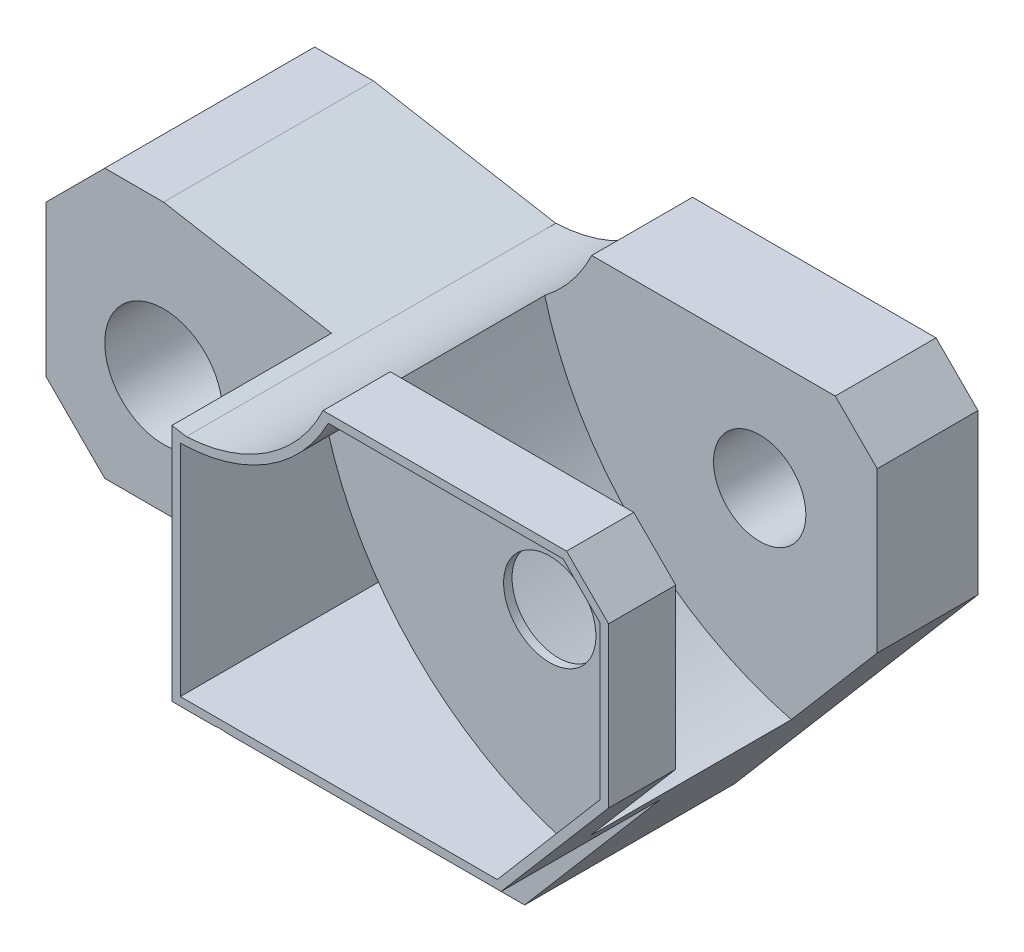
SolidWorks part; units mm, degrees
material "AISI 304"
ref_plane "Plan de face" through (0, 0, 0) normal (0, 0, 1) x (1, 0, 0)
ref_plane "Plan de dessus" through (0, 0, 0) normal (0, 1, 0) x (1, 0, 0)
ref_plane "Plan de droite" through (0, 0, 0) normal (1, 0, 0) x (0, 0, -1)
sketch "Esquisse1" plane through (0, 0, 0) normal (0, 0, 1) x (1, 0, 0)
  line L15 (69.0555, 42.5858) -> (98.0555, 42.5858)
  line L16 (98.0555, 42.5858) -> (103.0555, 37.5858)
  line L17 (103.0555, 37.5858) -> (103.0555, 18.5858)
  line L20 (103.0555, 18.5858) -> (74.0555, -15.4142)
  line L24 (31.0555, 35.5858) -> (52.7651, 31.7578)
  line L25 (31.0555, 35.5858) -> (24.0555, 35.5858)
  line L26 (24.0555, 35.5858) -> (17.0555, 28.5858)
  line L27 (17.0555, 28.5858) -> (17.0555, 10.5858)
  line L28 (17.0555, 10.5858) -> (24.0555, 3.5858)
  line L30 (24.0555, 3.5858) -> (56.0555, 3.5858)
  line L32 (74.0555, -15.4142) -> (68.3525, -15.4142)
  arc A4 (69.0555, 42.5858) -> (52.7651, 31.7578) centre (51.8932, 50.7378) cw
  arc A5 (56.0555, 3.5858) -> (61.7972, -1.9629) centre (56.8345, -1.3532) cw
  arc A7 (61.7972, -1.9629) -> (68.3525, -15.4142) centre (90.2614, 3.5858) ccw
  point P7 (90.2614, 3.5858)
  point P11 (71.204, -15.4142)
  dimension "D8" = 7
  dimension "D9" = 5
  dimension "D6" = 19
  dimension "D14" = 32
  dimension "D15" = 19
  dimension "D10" = 58
  dimension "D12" = 29
  dimension "D2" = 45
  dimension "D3" = 5
  dimension "D4" = 24
  dimension "D5" = 29
  dimension "D7" = 45
  dimension "D11" = 86
  dimension "D13" = 19
  dimension "D16" = 29
  dimension "D19" = 7
  dimension "D20" = 14
  dimension "D21" = 10
extrude "Boss.-Extru.1" add sketch "Esquisse1" along normal blind 44
sketch "Esquisse2" plane through (0, 0, 44) normal (0, 0, 1) x (1, 0, 0)
  line L0 (17.0555, 28.5858) -> (17.0555, 10.5858) construction
  line L1 (24.0555, 3.5858) -> (56.0555, 3.5858) construction
  circle A0 centre (31.0555, 17.5858) radius 7
  point P6 (35.5625, 11.703)
  dimension "D1" = 14
  dimension "D2" = 14
  dimension "D3" = 14
extrude "Enlèv. mat.-Extru.1" cut sketch "Esquisse2" against normal blind 44
sketch "Esquisse3" plane through (0, 0, 44) normal (0, 0, 1) x (1, 0, 0)
  line L0 (17.0555, 28.5858) -> (17.0555, 10.5858)
  line L1 (17.0555, 10.5858) -> (24.0555, 3.5858)
  line L2 (24.0555, 3.5858) -> (51.0555, 3.5858)
  line L3 (24.0555, 3.5858) -> (56.0555, 3.5858) construction
  line L4 (51.0555, 3.5858) -> (51.0555, 32.0592)
  line L5 (52.7651, 31.7578) -> (31.0555, 35.5858) construction
  line L6 (51.0555, 32.0592) -> (31.0555, 35.5858)
  line L7 (31.0555, 35.5858) -> (24.0555, 35.5858)
  line L8 (31.0555, 35.5858) -> (24.0555, 35.5858) construction
  line L9 (24.0555, 35.5858) -> (17.0555, 28.5858)
  dimension "D1" = 34
extrude "Enlèv. mat.-Extru.2" cut sketch "Esquisse3" against normal blind 19
sketch "Esquisse4" plane through (0, 0, 44) normal (0, 0, 1) x (1, 0, 0)
  line L0 (103.0555, 18.5858) -> (103.0555, 37.5858) construction
  line L1 (98.0555, 42.5858) -> (69.0555, 42.5858) construction
  circle A0 centre (89.0555, 28.5858) radius 5.5
  dimension "D1" = 11
  dimension "D2" = 14
  dimension "D3" = 14
extrude "Enlèv. mat.-Extru.3" cut sketch "Esquisse4" against normal blind 50
sketch "Esquisse10" plane through (0, 0, 44) normal (0, 0, 1) x (1, 0, 0)
  line L0 (56.0555, 3.5858) -> (90.2614, 3.5858)
  line L1 (74.0555, -15.4142) -> (103.0555, 18.5858) construction
  line L2 (90.2614, 3.5858) -> (74.0555, -15.4142)
  line L3 (74.0555, -15.4142) -> (68.3525, -15.4142)
  arc A0 (61.7972, -1.9629) -> (56.0555, 3.5858) centre (56.8345, -1.3532) ccw construction
  arc A1 (56.0555, 3.5858) -> (61.7972, -1.9629) centre (56.0555, -2.1592) cw
  arc A2 (61.7972, -1.9629) -> (68.3525, -15.4142) centre (90.2614, 3.5858) ccw
  point P15 (0, 0)
  dimension "D1" = 19
extrude "Enlèv. mat.-Extru.5" cut sketch "Esquisse10" against normal blind 19
sketch "Esquisse11" plane through (0, 0, 44) normal (0, 0, 1) x (1, 0, 0)
  line L0 (103.0555, 37.5858) -> (103.0555, 50.3291)
  line L1 (103.0555, 18.5858) -> (103.0555, 37.5858) construction
  line L2 (103.0555, 37.5858) -> (98.0555, 42.5858) construction
sketch "Esquisse13" plane through (0, 0, 44) normal (0, 0, 1) x (1, 0, 0)
  line L0 (103.0555, 37.5858) -> (103.0555, 50.3291) construction
  line L1 (90.2614, 3.5858) -> (103.0555, 18.5858) construction
  line L2 (98.0555, 42.5858) -> (69.0555, 42.5858) construction
  line L3 (69.0555, 42.5858) -> (98.0555, 42.5858)
  line L4 (98.0555, 42.5858) -> (103.0555, 37.5858)
  line L5 (103.0555, 37.5858) -> (103.0555, 18.5858)
  line L6 (103.0555, 18.5858) -> (92.8202, 6.5858)
  arc A0 (63.4564, 35.6616) -> (92.8202, 6.5858) centre (103.0555, 46.2877) ccw
  arc A1 (52.7651, 31.7578) -> (69.0555, 42.5858) centre (51.8932, 50.7378) ccw construction
  arc A2 (63.4564, 35.6616) -> (69.0555, 42.5858) centre (51.8932, 50.7378) ccw
  dimension "D2" = 41
  dimension "D1" = 36
extrude "Enlèv. mat.-Extru.8" cut sketch "Esquisse13" against normal blind 32
sketch "Esquisse14" plane through (0, 0, 44) normal (0, 0, 1) x (1, 0, 0)
  line L0 (92.8202, 6.5858) -> (103.0555, 18.5858)
  line L1 (103.0555, 18.5858) -> (103.0555, 37.5858)
  line L2 (103.0555, 37.5858) -> (98.0555, 42.5858)
  line L3 (98.0555, 42.5858) -> (69.0555, 42.5858)
  line L4 (103.0555, 37.5858) -> (103.0555, 50.3291) construction
  line L5 (90.2614, 3.5858) -> (92.8202, 6.5858) construction
  arc A0 (63.4564, 35.6616) -> (92.8202, 6.5858) centre (103.0555, 46.2877) ccw
  arc A1 (63.4564, 35.6616) -> (69.0555, 42.5858) centre (51.8932, 50.7378) ccw
  dimension "D2" = 41
  dimension "D1" = 36
extrude "Boss.-Extru.3" add sketch "Esquisse14" against normal blind 8
sketch "Esquisse15" plane through (0, 0, 44) normal (0, 0, 1) x (1, 0, 0)
  circle A0 centre (89.0555, 28.5858) radius 5.5
extrude "Enlèv. mat.-Extru.9" cut sketch "Esquisse15" against normal blind 44
sketch "Esquisse16" plane through (0, 0, 44) normal (0, 0, 1) x (1, 0, 0)
  line L0 (52.0555, 30.7384) -> (52.0555, 5.6949)
  line L1 (52.0555, 4.5858) -> (89.8, 4.5858)
  line L2 (99.8465, 16.3644) -> (102.0555, 18.9543)
  line L3 (102.0555, 19.2104) -> (102.0555, 37.1716)
  line L4 (102.0555, 37.1716) -> (97.6413, 41.5858)
  line L5 (90.2614, 3.5858) -> (57.6135, 3.5858) construction
  line L6 (51.0555, 3.5858) -> (51.0555, 32.0592) construction
  line L7 (52.0555, 5.6949) -> (52.0555, 4.5858)
  line L8 (90.2614, 3.5858) -> (103.0555, 18.5858) construction
  line L9 (89.8, 4.5858) -> (99.8465, 16.3644)
  line L10 (103.0555, 18.5858) -> (103.0555, 37.5858) construction
  line L11 (102.0555, 19.2104) -> (102.0555, 18.9543)
  line L12 (103.0555, 37.5858) -> (98.0555, 42.5858) construction
  line L13 (97.6413, 41.5858) -> (69.7927, 41.5858)
  line L14 (98.0555, 42.5858) -> (69.0555, 42.5858) construction
  line L15 (69.7927, 41.5858) -> (69.6764, 41.5858)
  arc A2 (52.0555, 30.7384) -> (69.6764, 41.5858) centre (51.8932, 50.7378) ccw
  dimension "D1" = 1
  dimension "D2" = 20
  dimension "D3" = 1
  dimension "D4" = 1
  dimension "D5" = 1
  dimension "D6" = 1
  dimension "D7" = 1
  dimension "D8" = 1
extrude "Enlèv. mat.-Extru.10" cut sketch "Esquisse16" against normal blind 7
sketch "Esquisse17" plane through (0, 0, 37) normal (0, 0, 1) x (1, 0, 0)
  line L0 (102.0555, 37.1716) -> (102.0555, 52.765)
  line L1 (89.8, 4.5858) -> (102.0555, 18.9543) construction
  line L2 (97.6413, 41.5858) -> (69.6764, 41.5858) construction
  line L3 (52.0555, 30.7384) -> (52.0555, 4.5858)
  line L4 (52.0555, 4.5858) -> (89.8, 4.5858)
  line L5 (89.8, 4.5858) -> (90.6529, 5.5858)
  arc A0 (62.5942, 33.8414) -> (90.6529, 5.5858) centre (102.0555, 44.9683) ccw
  arc A1 (52.0555, 30.7384) -> (69.6764, 41.5858) centre (51.8932, 50.7378) ccw construction
  arc A2 (52.0555, 30.7384) -> (62.5942, 33.8414) centre (51.8932, 50.7378) ccw
  arc M6 (69.6764, 41.5858) -> (52.0555, 30.7384) centre (51.8932, 50.7378) cw
  line M7 (52.0555, 30.7384) -> (52.0555, 4.5858)
  line M8 (52.0555, 4.5858) -> (89.8, 4.5858)
  line M9 (89.8, 4.5858) -> (102.0555, 18.9543)
  dimension "D2" = 41
  dimension "D1" = 36
extrude "Enlèv. mat.-Extru.11" cut sketch "Esquisse17" against normal blind 32 contours A0 M6 M7 M8 M9
